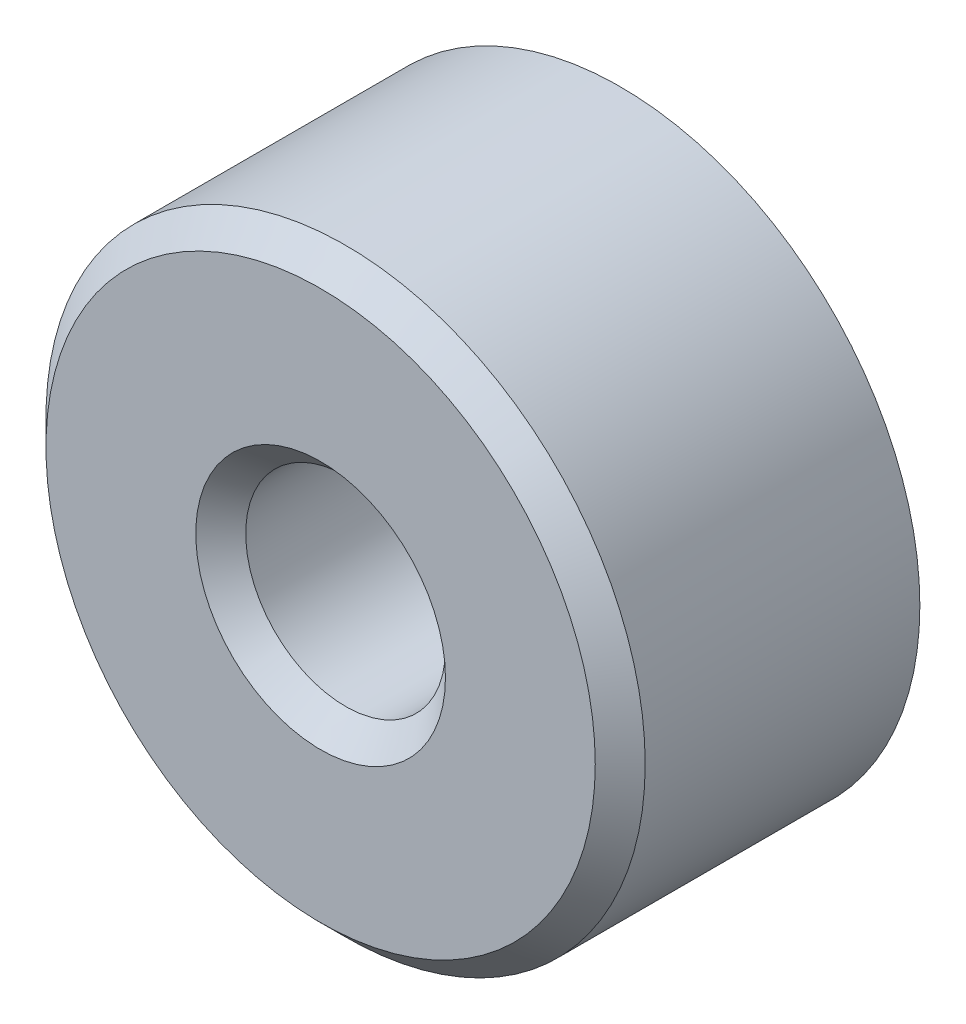
SolidWorks part; units mm, degrees
ref_plane "Front Plane" through (0, 0, 0) normal (0, 0, 1) x (1, 0, 0)
ref_plane "Top Plane" through (0, 0, 0) normal (0, 1, 0) x (1, 0, 0)
ref_plane "Right Plane" through (0, 0, 0) normal (1, 0, 0) x (0, 0, -1)
sketch "Sketch1" plane through (0, 0, 0) normal (0, 0, 1) x (1, 0, 0)
  circle A0 centre (0, 0) radius 1
  dimension "D1" = 2
extrude "Extrude-Thin1" add sketch "Sketch1" along normal blind 3 thin contours A0
chamfer "Chamfer1" distance 0.25 angle 45 1 edges at (3, 0, 3)
chamfer "Chamfer2" distance 0.25 angle 45 1 edges at (1, 0, 3)
